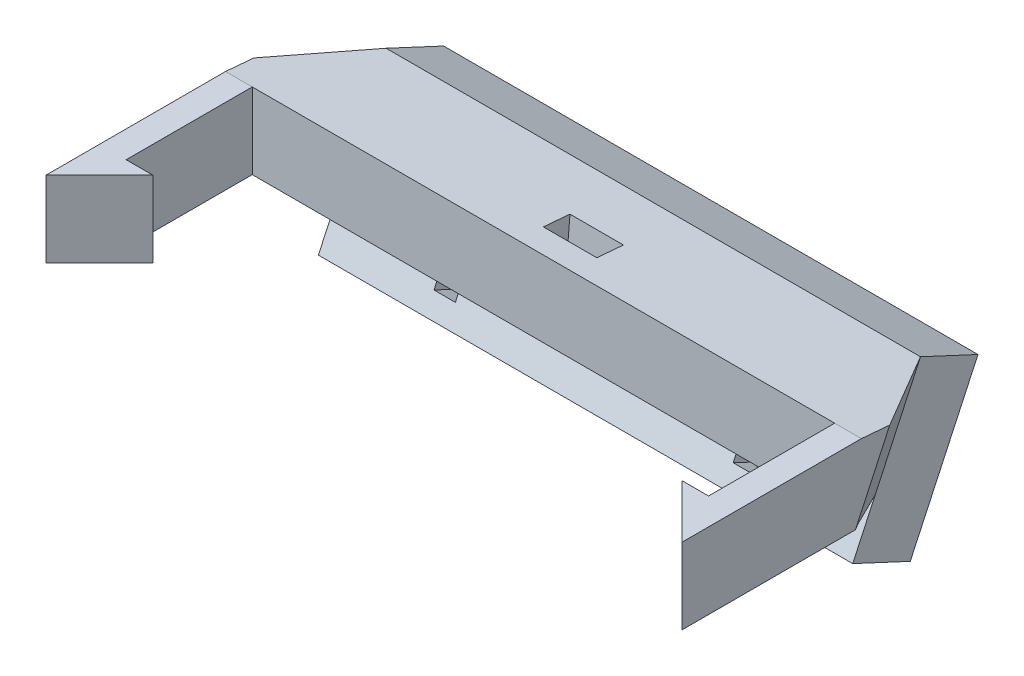
SolidWorks part; units mm, degrees
ref_plane "Front Plane" through (0, 0, 0) normal (0, 0, 1) x (1, 0, 0)
ref_plane "Top Plane" through (0, 0, 0) normal (0, 1, 0) x (1, 0, 0)
ref_plane "Right Plane" through (0, 0, 0) normal (1, 0, 0) x (0, 0, -1)
sketch "Sketch1" plane through (0, 0, 0) normal (0, 0, 1) x (1, 0, 0)
  line L1 (-37.7825, 17.78) -> (37.7825, 17.78)
  line L2 (-37.7825, 17.78) -> (-37.7825, -17.78)
  line L3 (-37.7825, -17.78) -> (37.7825, -17.78)
  line L4 (37.7825, 17.78) -> (37.7825, -17.78)
  point P4 (0, 17.78)
  point P6 (-37.7825, 0)
  dimension "D1" = 75.565
extrude "Boss-Extrude1" add sketch "Sketch1" against normal blind 3.175
sketch "Sketch6" plane through (0, 0, 0) normal (0, 0, 1) x (1, 0, 0)
  line L0 (-37.7825, 17.78) -> (-37.7825, -17.78) construction
  line L1 (-37.7825, 4.5142) -> (-34.6075, 4.5142)
  line L2 (-37.7825, 4.5142) -> (-37.7825, -4.5142)
  line L3 (-37.7825, -4.5142) -> (-34.6075, -4.5142)
  line L4 (-34.6075, 4.5142) -> (-34.6075, -4.5142)
  line L5 (37.7825, -17.78) -> (37.7825, 17.78) construction
  line L6 (37.7825, 4.5142) -> (34.6075, 4.5142)
  line L7 (37.7825, 4.5142) -> (37.7825, -4.5142)
  line L8 (37.7825, -4.5142) -> (34.6075, -4.5142)
  line L9 (34.6075, 4.5142) -> (34.6075, -4.5142)
  point P12 (37.7825, 0)
  point P14 (-37.7825, 0)
  dimension "D1" = 3.175
  dimension "D2" = 3.175
  dimension "D3" = 69.215
extrude "Boss-Extrude4" add sketch "Sketch6" along normal blind 14.986
sketch "Sketch8" plane through (0, -4.5142, 0) normal (0, -1, 0) x (1, 0, 0)
  line L0 (-37.7825, 14.986) -> (-31.4325, 14.986)
  line L1 (-31.4325, 14.986) -> (-37.7825, 21.336)
  line L2 (-37.7825, 21.336) -> (-37.7825, 14.986)
  line L3 (37.7825, 14.986) -> (31.4325, 14.986)
  line L4 (31.4325, 14.986) -> (37.7825, 21.336)
  line L5 (37.7825, 21.336) -> (37.7825, 14.986)
  dimension "D1" = 6.35
  dimension "D2" = 6.35
  dimension "D3" = 6.35
  dimension "D4" = 6.35
extrude "Boss-Extrude6" add sketch "Sketch8" against normal up to surface (9.0284 mm away) up to face at (-36.195, 4.5142, 7.493)
sketch "Sketch9" plane through (-37.7825, 0, 0) normal (-1, 0, 0) x (0, 0, 1)
  line L0 (-3.175, 17.78) -> (-16.7953, 11.4288)
  line L1 (-16.7953, 11.4288) -> (-3.175, -17.78)
  line L3 (-3.175, 17.78) -> (-3.175, -17.78) construction
  line L12 (0, 4.5142) -> (0, 17.78)
  line L13 (0, 17.78) -> (-3.175, 17.78)
  line L14 (-3.175, 17.78) -> (-3.175, -17.78)
  line L15 (-3.175, -17.78) -> (0, -17.78)
  line L16 (0, -17.78) -> (0, -4.5142)
  line L17 (0, -4.5142) -> (21.336, -4.5142)
  line L18 (21.336, -4.5142) -> (21.336, 4.5142)
  line L19 (21.336, 4.5142) -> (0, 4.5142)
  line L22 (-3.175, 17.78) -> (-3.175, -17.78)
  dimension "D1" = 90
  dimension "D2" = 25
  dimension "D3" = 0
extrude "Boss-Extrude7" add sketch "Sketch9" against normal up to surface (75.565 mm away) up to face at (37.7825, 0, 4.5403)
sketch "Sketch10" plane through (0, -4.3917, -9.4181) normal (0, -0.4226, -0.9063) x (-1, 0, 0)
  line L0 (37.7825, 17.456) -> (37.7825, -14.7723) construction
  line L1 (-37.7825, -14.7723) -> (37.7825, -14.7723)
  line L2 (-37.7825, -14.7723) -> (-37.7825, 8.5957)
  line L3 (-37.7825, 8.5957) -> (37.7825, 8.5957)
  line L4 (37.7825, -14.7723) -> (37.7825, 8.5957)
  dimension "D1" = 23.368
extrude "Boss-Extrude8" add sketch "Sketch10" along normal blind 7.5452
sketch "Sketch11" plane through (-37.7825, 0, 0) normal (-1, 0, 0) x (0, 0, 1)
  line L0 (-13.0507, 3.3986) -> (0, 4.5142)
  line L1 (0, 4.5142) -> (36.8887, 18.2755)
  line L2 (36.8887, 18.2755) -> (5.2861, 25.1503)
  line L3 (5.2861, 25.1503) -> (-30.3838, 8.2332)
  line L4 (-30.3838, 8.2332) -> (-13.0507, 3.3986)
  line L5 (-3.175, -17.78) -> (-7.689, -8.0996)
  line L6 (-7.689, -8.0996) -> (0, -4.5142)
  line L7 (0, -4.5142) -> (40.1585, -20.4064)
  line L8 (40.1585, -20.4064) -> (15.5997, -25.3949)
  line L9 (15.5997, -25.3949) -> (-3.175, -17.78)
  line L10 (-10.0132, -20.9687) -> (-19.889, 0.2099) construction
  line L11 (-10.0132, -20.9687) -> (-3.175, -17.78) construction
extrude "Cut-Extrude1" cut sketch "Sketch11" against normal through all
sketch "Sketch12" plane through (0, 4.4814, -0.3831) normal (0, 0.9964, -0.0852) x (1, 0, 0)
  line L0 (34.6075, -0.3845) -> (-34.6075, -0.3845) construction
  line L1 (-3.175, 5.9655) -> (3.175, 5.9655)
  line L2 (-3.175, 5.9655) -> (-3.175, 2.7905)
  line L3 (-3.175, 2.7905) -> (3.175, 2.7905)
  line L4 (3.175, 5.9655) -> (3.175, 2.7905)
  point P6 (0, 2.7905)
  point P7 (0, -0.3845)
  dimension "D1" = 3.175
  dimension "D2" = 6.35
  dimension "D3" = 3.175
extrude "Cut-Extrude2" cut sketch "Sketch12" against normal up to next and the other way through all
sketch "Sketch13" plane through (0, 7.7903, -3.6327) normal (0, 0.9063, -0.4226) x (1, 0, 0)
  line L0 (0, 10.3917) -> (0, 17.9368) construction
  line L1 (-37.7825, 10.3917) -> (37.7825, 10.3917) construction
  line L2 (-37.7825, 17.9368) -> (37.7825, 17.9368) construction
  line L3 (-31.75, 10.3917) -> (-37.7825, 1.2672)
  line L4 (-37.7825, 17.9368) -> (-31.75, 17.9368)
  line L5 (-37.7825, 17.9368) -> (-37.7825, 11.6396)
  line L6 (37.7825, 1.2672) -> (37.7825, 11.6396)
  line L7 (-31.75, 17.9368) -> (-31.75, 10.3917)
  line L8 (-37.7825, 1.2672) -> (-37.7825, 11.6396)
  line L9 (37.7825, 17.9368) -> (37.7825, 11.6396)
  line L10 (37.7825, 17.9368) -> (31.75, 17.9368)
  line L11 (31.75, 10.3917) -> (37.7825, 1.2672)
  line L12 (31.75, 17.9368) -> (31.75, 10.3917)
  line L13 (-37.7825, 10.3917) -> (-37.7825, -1.9078) construction
  point P12 (-31.75, 14.1643)
  dimension "D1" = 63.5
  dimension "D2" = 3.175
extrude "Cut-Extrude3" cut sketch "Sketch13" against normal through all
sketch "Sketch14" plane through (0, -7.5804, -16.2563) normal (0, -0.4226, -0.9063) x (-1, 0, 0)
  line L0 (-31.75, -4.1779) -> (31.75, -4.1779) construction
  line L1 (-31.75, -14.7723) -> (-31.75, 8.5957) construction
  line L2 (0, -4.1779) -> (0, -14.7723) construction
  line L3 (-19.05, -4.1779) -> (-16.51, -4.1779)
  line L4 (-19.05, -4.1779) -> (-19.05, -7.9879)
  line L5 (-19.05, -7.9879) -> (-16.51, -7.9879)
  line L6 (-16.51, -4.1779) -> (-16.51, -7.9879)
  line L7 (-31.75, -14.7723) -> (31.75, -14.7723) construction
  line L8 (19.05, -4.1779) -> (16.51, -4.1779)
  line L9 (16.51, -4.1779) -> (16.51, -7.9879)
  line L10 (19.05, -7.9879) -> (16.51, -7.9879)
  line L11 (19.05, -4.1779) -> (19.05, -7.9879)
  line L12 (-25.4, -11.0373) -> (0, -11.0373) construction
  dimension "D1" = 2.54
  dimension "D2" = 3.81
  dimension "D3" = 25.4
  dimension "D4" = 6.35
extrude "Cut-Extrude4" cut sketch "Sketch14" against normal up to next
sketch "Sketch15" plane through (0, -7.5804, -16.2563) normal (0, -0.4226, -0.9063) x (-1, 0, 0)
  line L0 (31.75, 8.5957) -> (-31.75, 8.5957) construction
  line L1 (-65.0097, -10.4543) -> (49.6515, -10.4543)
  line L2 (-65.0097, -10.4543) -> (-65.0097, -16.0708)
  line L3 (-65.0097, -16.0708) -> (49.6515, -16.0708)
  line L4 (49.6515, -10.4543) -> (49.6515, -16.0708)
  dimension "D1" = 19.05
extrude "Cut-Extrude5" cut sketch "Sketch15" against normal up to next
